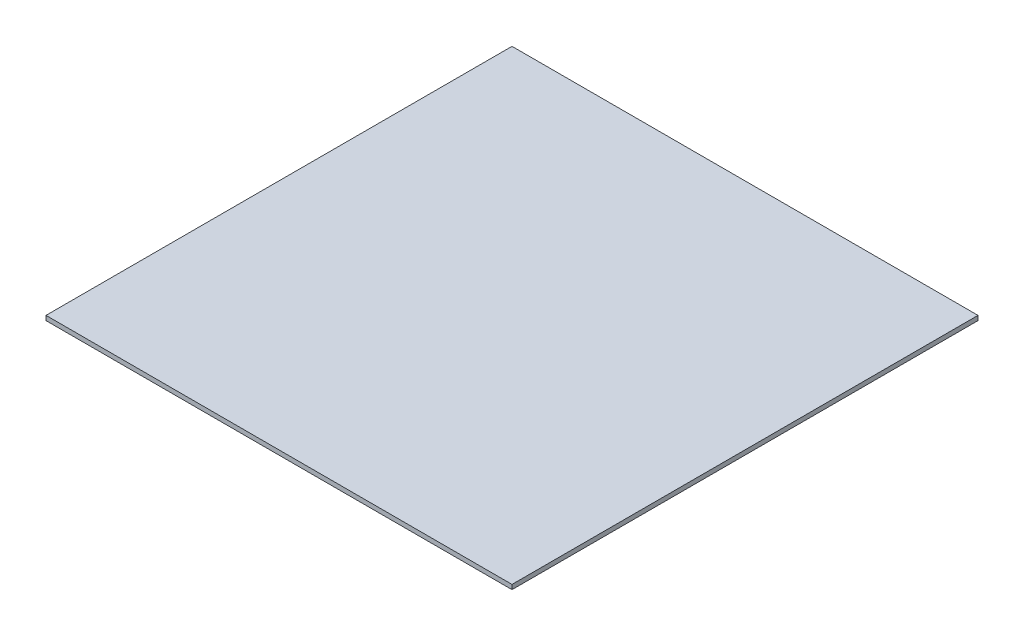
SolidWorks part; units mm, degrees
ref_plane "Front Plane" through (0, 0, 0) normal (0, 0, 1) x (1, 0, 0)
ref_plane "Top Plane" through (0, 0, 0) normal (0, 1, 0) x (1, 0, 0)
ref_plane "Right Plane" through (0, 0, 0) normal (1, 0, 0) x (0, 0, -1)
sketch "Sketch1" plane through (0, 0, 0) normal (0, 1, 0) x (1, 0, 0)
  line L1 (-647.7, -647.7) -> (647.7, -647.7)
  line L2 (-647.7, -647.7) -> (-647.7, 647.7)
  line L3 (-647.7, 647.7) -> (647.7, 647.7)
  line L4 (647.7, -647.7) -> (647.7, 647.7)
  line L5 (-647.7, -647.7) -> (647.7, 647.7) construction
  line L6 (-647.7, 647.7) -> (647.7, -647.7) construction
  point P0 (0, 0)
  dimension "D1" = 1295.4
extrude "Boss-Extrude1" add sketch "Sketch1" along normal blind 12.7
